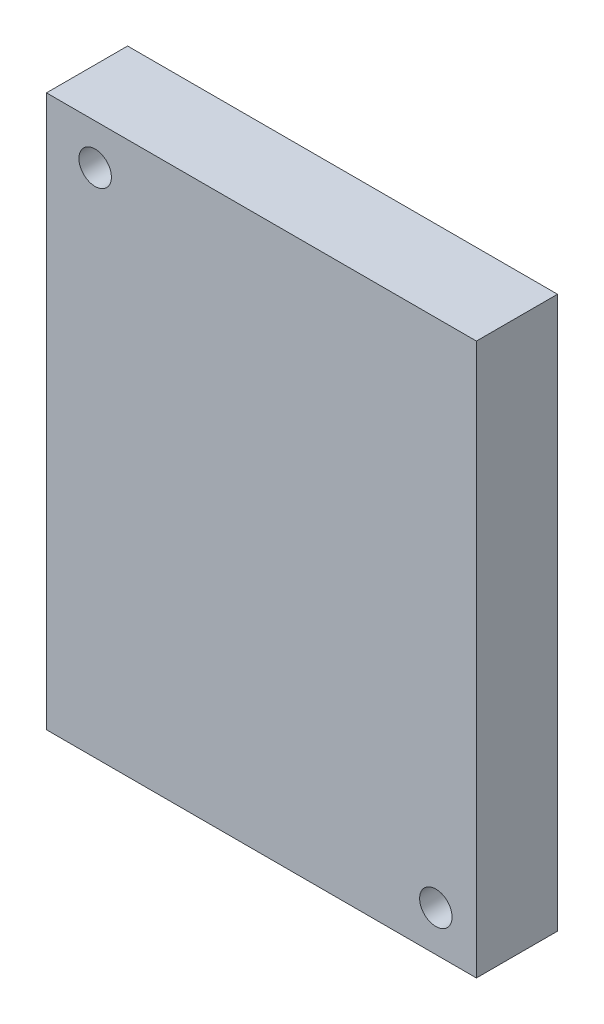
SolidWorks part; units mm, degrees
ref_plane "Front Plane" through (0, 0, 0) normal (0, 0, 1) x (1, 0, 0)
ref_plane "Top Plane" through (0, 0, 0) normal (0, 1, 0) x (1, 0, 0)
ref_plane "Right Plane" through (0, 0, 0) normal (1, 0, 0) x (0, 0, -1)
sketch "Sketch1" plane through (0, 0, 0) normal (0, 0, 1) x (1, 0, 0)
  line L1 (0, 0) -> (26.5, 0)
  line L2 (0, 0) -> (0, 34)
  line L3 (0, 34) -> (26.5, 34)
  line L4 (26.5, 0) -> (26.5, 34)
  circle A0 centre (3, 31.5) radius 1
  circle A1 centre (24, 2.5) radius 1
  point P7 (2, 31.5)
  point P8 (3, 32.5)
  point P11 (24, 1.5)
  point P12 (25, 2.5)
  dimension "D3" = 2
  dimension "D6" = 2
  dimension "D1" = 26.5
  dimension "D2" = 34
  dimension "D4" = 2
  dimension "D5" = 1.5
  dimension "D7" = 1.5
  dimension "D8" = 1.5
extrude "Boss-Extrude1" add sketch "Sketch1" along normal blind 5
